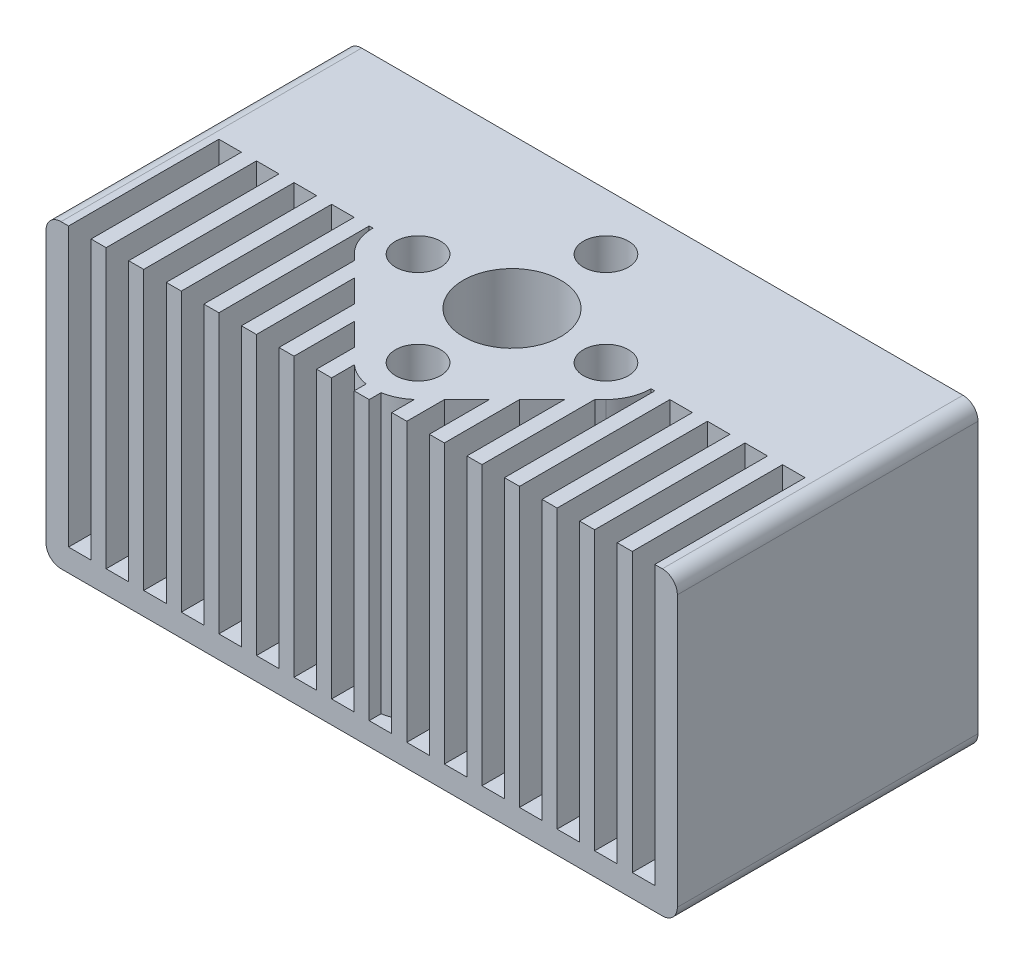
SolidWorks part; units mm, degrees
ref_plane "Front Plane" through (0, 0, 0) normal (0, 0, 1) x (1, 0, 0)
ref_plane "Top Plane" through (0, 0, 0) normal (0, 1, 0) x (1, 0, 0)
ref_plane "Right Plane" through (0, 0, 0) normal (1, 0, 0) x (0, 0, -1)
sketch "Sketch1" plane through (0, 0, 0) normal (0, 0, 1) x (1, 0, 0)
  line L1 (-42, 20) -> (42, 20)
  line L2 (-42, 20) -> (-42, -20)
  line L3 (-42, -20) -> (42, -20)
  line L4 (42, 20) -> (42, -20)
  line L5 (-42, 20) -> (42, -20) construction
  line L6 (-42, -20) -> (42, 20) construction
  point P0 (0, 0)
  dimension "D1" = 40
  dimension "D2" = 84
extrude "Boss-Extrude1" add sketch "Sketch1" along normal mid plane 40
fillet "Fillet1" radius 2 4 edges at (-42, 20, 0) (-42, -20, 0) (42, -20, 0) (42, 20, 0)
sketch "Sketch3" plane through (0, 20, 0) normal (0, 1, 0) x (1, 0, 0)
  point P0 (0, 0)
hole_wizard "Hole1" positions "Sketch3" profile "Sketch4" legacy end condition through all
sketch "Sketch4" plane through (0, 20, 0) normal (1, 0, 0) x (0, 0, 1)
  line L0 (0, 0) -> (0, 40)
  line L1 (0, 40) -> (6.5, 40)
  line L2 (6.5, 40) -> (6.5, 0)
  line L3 (6.5, 0) -> (0, 0)
  line L4 (0, 110) -> (0, -10) construction
  dimension "Diameter" = 13
  dimension "Depth" = 40
sketch "Sketch5" plane through (0, 20, 0) normal (0, 1, 0) x (1, 0, 0)
  point P0 (12.5, 0)
  point P4 (0, -12.5)
  point P5 (-12.5, 0)
  point P6 (0, 12.5)
  point P7 (0, 0)
  dimension "D2" = 25
  dimension "D1" = 4
hole_wizard "Hole2" positions "Sketch5" profile "Sketch6" legacy end condition through all
sketch "Sketch6" plane through (12.5, 20, 0) normal (1, 0, 0) x (0, 0, 1)
  line L0 (0, 0) -> (0, 40)
  line L1 (0, 40) -> (3, 40)
  line L2 (3, 40) -> (3, 0)
  line L3 (3, 0) -> (0, 0)
  line L4 (0, 110) -> (0, -10) construction
  dimension "Diameter" = 6
  dimension "Depth" = 40
sketch "Sketch9" plane through (0, 0, 0) normal (0, 1, 0) x (1, 0, 0)
  line L0 (18.5, 0) -> (39, 0)
  line L1 (4.2426, -16.7426) -> (16.7426, -4.2426)
  line L2 (39, 0) -> (39, -20)
  line L3 (39, -20) -> (-39, -20)
  line L4 (-40, -20) -> (40, -20) construction
  line L5 (0, -20) -> (0, -18.5)
  line L6 (42, 20) -> (42, -20) construction
  line L7 (0, -22) -> (0, 22) construction
  line L8 (-4.2426, -16.7426) -> (-16.7426, -4.2426)
  line L9 (-39, 0) -> (-39, -20)
  line L10 (-18.5, 0) -> (-39, 0)
  circle A0 centre (0, 0) radius 6.5
  circle A1 centre (0, 0) radius 6.5 construction
  circle A2 centre (-12.5, 0) radius 3
  circle A3 centre (-12.5, 0) radius 3 construction
  circle A4 centre (0, 12.5) radius 3
  circle A5 centre (0, 12.5) radius 3 construction
  circle A6 centre (12.5, 0) radius 3
  circle A7 centre (12.5, 0) radius 3 construction
  circle A8 centre (0, -12.5) radius 3
  circle A9 centre (0, -12.5) radius 3 construction
  arc A10 (-4.2426, -16.7426) -> (4.2426, -16.7426) centre (0, -12.5) ccw
  arc A11 (16.7426, -4.2426) -> (18.5, 0) centre (12.5, 0) ccw
  arc A13 (0, -6.5) -> (0, -18.5) centre (0, -12.5) ccw construction
  circle A14 centre (0, -12.5) radius 6 construction
  arc A15 (18.5, 0) -> (6.5, 0) centre (12.5, 0) ccw construction
  circle A16 centre (12.5, 0) radius 6 construction
  arc A17 (6.5, 0) -> (12.5, -6) centre (12.5, 0) ccw construction
  arc A18 (6, -12.5) -> (0, -6.5) centre (0, -12.5) ccw construction
  arc A19 (4.2426, -16.7426) -> (6, -12.5) centre (0, -12.5) ccw construction
  arc A20 (12.5, -6) -> (16.7426, -4.2426) centre (12.5, 0) ccw construction
  arc A21 (-16.7426, -4.2426) -> (-18.5, 0) centre (-12.5, 0) cw
  dimension "D1" = 3
  dimension "D3" = 3
  dimension "D2" = 3
extrude "Cut-Extrude2" cut sketch "Sketch9" against normal mid plane 34 contours L8 A21 L10 L9 L3 L5 A10 | A11 L1 A10 L5 L3 L2 L0
sketch "Sketch10" plane through (0, 0, 20) normal (0, 0, 1) x (1, 0, 0)
  line L0 (0, -17) -> (0, 17)
  line L1 (4.2426, -17) -> (-4.2426, -17) construction
  line L2 (-4.2426, 17) -> (4.2426, 17) construction
  line L3 (5, -17) -> (5, 17)
  line L4 (10, -17) -> (10, 17)
  line L5 (15, -17) -> (15, 17)
  line L6 (20, -17) -> (20, 17)
  line L7 (25, -17) -> (25, 17)
  line L8 (30, -17) -> (30, 17)
  line L9 (35, -17) -> (35, 17)
  line L10 (0, -22) -> (0, 22) construction
  line L11 (-25, -17) -> (-25, 17)
  line L12 (-20, -17) -> (-20, 17)
  line L13 (-15, -17) -> (-15, 17)
  line L14 (-10, -17) -> (-10, 17)
  line L15 (-5, -17) -> (-5, 17)
  line L16 (-30, -17) -> (-30, 17)
  line L17 (-35, -17) -> (-35, 17)
  dimension "D1" = 8
  dimension "D2" = 5
rib "Rib1" sketch "Sketch10" sketch "Sketch10" thickness 2 extrusion direction normal to sketch draft on no parameters "D1"=2
sketch "Sketch12" plane through (0, 17, 0) normal (0, -1, 0) x (1, 0, 0)
  line L0 (36, 20) -> (36, 0) construction
  line L1 (36, 0) -> (39, 0) construction
  line L2 (39, 0) -> (39, 20) construction
  line L3 (39, 20) -> (36, 20) construction
  line L4 (31, 0) -> (34, 0) construction
  line L5 (34, 0) -> (34, 20) construction
  line L6 (34, 20) -> (31, 20) construction
  line L7 (31, 20) -> (31, 0) construction
  line L8 (26, 0) -> (29, 0) construction
  line L9 (29, 0) -> (29, 20) construction
  line L10 (29, 20) -> (26, 20) construction
  line L11 (26, 20) -> (26, 0) construction
  line L12 (21, 0) -> (24, 0) construction
  line L13 (24, 0) -> (24, 20) construction
  line L14 (24, 20) -> (21, 20) construction
  line L15 (21, 20) -> (21, 0) construction
  line L16 (18.5, 0) -> (19, 0) construction
  line L17 (19, 0) -> (19, 20) construction
  line L18 (19, 20) -> (16, 20) construction
  line L19 (16, 20) -> (16, 4.9853) construction
  line L20 (16, 4.9853) -> (16.7426, 4.2426) construction
  line L21 (11, 9.9853) -> (14, 6.9853) construction
  line L22 (14, 6.9853) -> (14, 20) construction
  line L23 (14, 20) -> (11, 20) construction
  line L24 (11, 20) -> (11, 9.9853) construction
  line L25 (6, 14.9853) -> (9, 11.9853) construction
  line L26 (9, 11.9853) -> (9, 20) construction
  line L27 (9, 20) -> (6, 20) construction
  line L28 (6, 20) -> (6, 14.9853) construction
  line L29 (4, 16.9721) -> (4, 20) construction
  line L30 (4, 20) -> (1, 20) construction
  line L31 (1, 20) -> (1, 18.4161) construction
  line L32 (-4, 20) -> (-4, 16.9721) construction
  line L33 (-1, 18.4161) -> (-1, 20) construction
  line L34 (-1, 20) -> (-4, 20) construction
  line L35 (-9, 11.9853) -> (-6, 14.9853) construction
  line L36 (-6, 14.9853) -> (-6, 20) construction
  line L37 (-6, 20) -> (-9, 20) construction
  line L38 (-9, 20) -> (-9, 11.9853) construction
  line L39 (-14, 6.9853) -> (-11, 9.9853) construction
  line L40 (-11, 9.9853) -> (-11, 20) construction
  line L41 (-11, 20) -> (-14, 20) construction
  line L42 (-14, 20) -> (-14, 6.9853) construction
  line L43 (-16.7426, 4.2426) -> (-16, 4.9853) construction
  line L44 (-16, 4.9853) -> (-16, 20) construction
  line L45 (-16, 20) -> (-19, 20) construction
  line L46 (-19, 20) -> (-19, 0) construction
  line L47 (-19, 0) -> (-18.5, 0) construction
  line L48 (-24, 0) -> (-21, 0) construction
  line L49 (-21, 0) -> (-21, 20) construction
  line L50 (-21, 20) -> (-24, 20) construction
  line L51 (-24, 20) -> (-24, 0) construction
  line L52 (-29, 20) -> (-29, 0) construction
  line L53 (-29, 0) -> (-26, 0) construction
  line L54 (-26, 0) -> (-26, 20) construction
  line L55 (-26, 20) -> (-29, 20) construction
  line L56 (-34, 20) -> (-34, 0) construction
  line L57 (-34, 0) -> (-31, 0) construction
  line L58 (-31, 0) -> (-31, 20) construction
  line L59 (-31, 20) -> (-34, 20) construction
  line L60 (-39, 0) -> (-36, 0) construction
  line L61 (-36, 0) -> (-36, 20) construction
  line L62 (-36, 20) -> (-39, 20) construction
  line L63 (-39, 20) -> (-39, 0) construction
  line L64 (36, 20) -> (36, 0)
  line L65 (36, 0) -> (39, 0)
  line L66 (39, 0) -> (39, 20)
  line L67 (39, 20) -> (36, 20)
  line L68 (31, 0) -> (34, 0)
  line L69 (34, 0) -> (34, 20)
  line L70 (34, 20) -> (31, 20)
  line L71 (31, 20) -> (31, 0)
  line L72 (26, 0) -> (29, 0)
  line L73 (29, 0) -> (29, 20)
  line L74 (29, 20) -> (26, 20)
  line L75 (26, 20) -> (26, 0)
  line L76 (21, 0) -> (24, 0)
  line L77 (24, 0) -> (24, 20)
  line L78 (24, 20) -> (21, 20)
  line L79 (21, 20) -> (21, 0)
  line L80 (18.5, 0) -> (19, 0)
  line L81 (19, 0) -> (19, 20)
  line L82 (19, 20) -> (16, 20)
  line L83 (16, 20) -> (16, 4.9853)
  line L84 (16, 4.9853) -> (16.7426, 4.2426)
  line L85 (11, 9.9853) -> (14, 6.9853)
  line L86 (14, 6.9853) -> (14, 20)
  line L87 (14, 20) -> (11, 20)
  line L88 (11, 20) -> (11, 9.9853)
  line L89 (6, 14.9853) -> (9, 11.9853)
  line L90 (9, 11.9853) -> (9, 20)
  line L91 (9, 20) -> (6, 20)
  line L92 (6, 20) -> (6, 14.9853)
  line L93 (4, 16.9721) -> (4, 20)
  line L94 (4, 20) -> (1, 20)
  line L95 (1, 20) -> (1, 18.4161)
  line L96 (-4, 20) -> (-4, 16.9721)
  line L97 (-1, 18.4161) -> (-1, 20)
  line L98 (-1, 20) -> (-4, 20)
  line L99 (-9, 11.9853) -> (-6, 14.9853)
  line L100 (-6, 14.9853) -> (-6, 20)
  line L101 (-6, 20) -> (-9, 20)
  line L102 (-9, 20) -> (-9, 11.9853)
  line L103 (-14, 6.9853) -> (-11, 9.9853)
  line L104 (-11, 9.9853) -> (-11, 20)
  line L105 (-11, 20) -> (-14, 20)
  line L106 (-14, 20) -> (-14, 6.9853)
  line L107 (-16.7426, 4.2426) -> (-16, 4.9853)
  line L108 (-16, 4.9853) -> (-16, 20)
  line L109 (-16, 20) -> (-19, 20)
  line L110 (-19, 20) -> (-19, 0)
  line L111 (-19, 0) -> (-18.5, 0)
  line L112 (-24, 0) -> (-21, 0)
  line L113 (-21, 0) -> (-21, 20)
  line L114 (-21, 20) -> (-24, 20)
  line L115 (-24, 20) -> (-24, 0)
  line L116 (-29, 20) -> (-29, 0)
  line L117 (-29, 0) -> (-26, 0)
  line L118 (-26, 0) -> (-26, 20)
  line L119 (-26, 20) -> (-29, 20)
  line L120 (-34, 20) -> (-34, 0)
  line L121 (-34, 0) -> (-31, 0)
  line L122 (-31, 0) -> (-31, 20)
  line L123 (-31, 20) -> (-34, 20)
  line L124 (-39, 0) -> (-36, 0)
  line L125 (-36, 0) -> (-36, 20)
  line L126 (-36, 20) -> (-39, 20)
  line L127 (-39, 20) -> (-39, 0)
  arc A0 (18.5, 0) -> (16.7426, 4.2426) centre (12.5, 0) ccw construction
  arc A1 (4, 16.9721) -> (1, 18.4161) centre (0, 12.5) ccw construction
  arc A2 (-1, 18.4161) -> (-4, 16.9721) centre (0, 12.5) ccw construction
  arc A3 (-16.7426, 4.2426) -> (-18.5, 0) centre (-12.5, 0) ccw construction
  arc A4 (18.5, 0) -> (16.7426, 4.2426) centre (12.5, 0) ccw
  arc A5 (4, 16.9721) -> (1, 18.4161) centre (0, 12.5) ccw
  arc A6 (-1, 18.4161) -> (-4, 16.9721) centre (0, 12.5) ccw
  arc A7 (-16.7426, 4.2426) -> (-18.5, 0) centre (-12.5, 0) ccw
extrude "Cut-Extrude3" cut sketch "Sketch12" against normal through all
